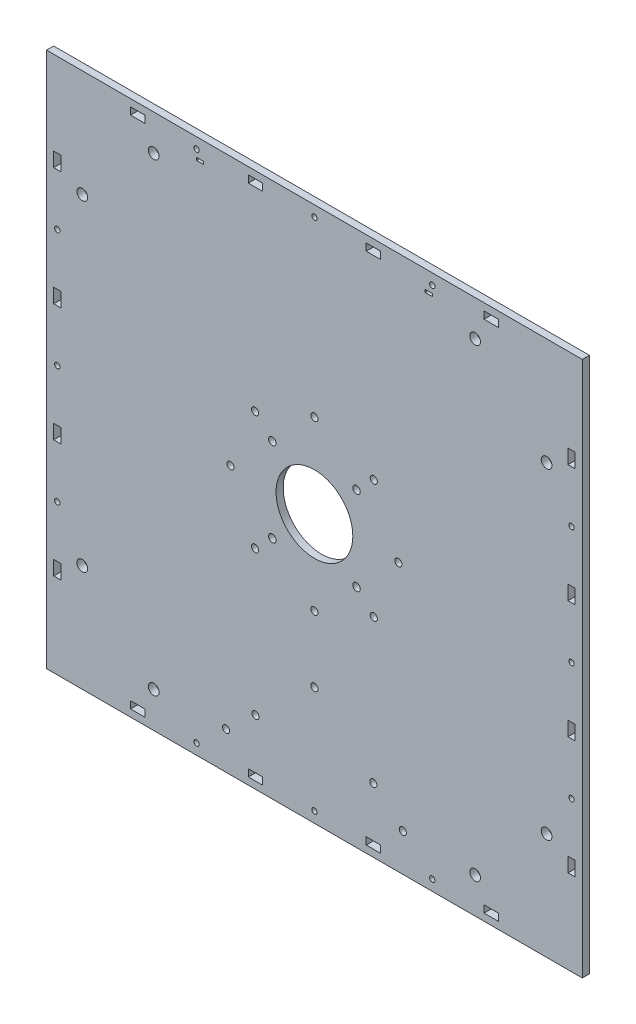
SolidWorks part; units mm, degrees
ref_plane "前视基准面" through (0, 0, 0) normal (0, 0, 1) x (1, 0, 0)
ref_plane "上视基准面" through (0, 0, 0) normal (0, 1, 0) x (1, 0, 0)
ref_plane "右视基准面" through (0, 0, 0) normal (1, 0, 0) x (0, 0, -1)
sketch "草图1" plane through (0, 0, 0) normal (0, 0, 1) x (1, 0, 0)
  line L0 (1.4571, -21.1871) -> (1.4571, -41.1871) construction
  line L1 (63.4571, 98.8129) -> (67.4571, 98.8129)
  line L2 (1.4571, -21.1871) -> (1.4571, 44.8129) construction
  line L3 (67.4571, 98.8129) -> (67.4571, 97.3129)
  line L4 (151.4571, -41.1871) -> (151.4571, 108.8129)
  line L5 (151.4571, 108.8129) -> (-148.5429, 108.8129)
  line L6 (-148.5429, 108.8129) -> (-148.5429, -191.1871)
  line L7 (-148.5429, -191.1871) -> (151.4571, -191.1871)
  line L8 (151.4571, -191.1871) -> (151.4571, -41.1871)
  line L9 (-148.5429, -41.1871) -> (-161.9412, -41.1871) construction
  line L10 (1.4571, -191.1871) -> (1.4571, -181.0361) construction
  line L11 (67.4571, 97.3129) -> (63.4571, 97.3129)
  line L12 (63.4571, 97.3129) -> (63.4571, 98.8129)
  line L13 (-64.5429, 98.8129) -> (-64.5429, 97.3129)
  line L14 (-64.5429, 97.3129) -> (-60.5429, 97.3129)
  line L15 (-60.5429, 97.3129) -> (-60.5429, 98.8129)
  line L16 (-60.5429, 98.8129) -> (-64.5429, 98.8129)
  circle A6 centre (1.4571, -21.1871) radius 241.4173 construction
  circle A9 centre (1.4571, -41.1871) radius 21.5
  circle A10 centre (25.0271, -17.6171) radius 2.1
  circle A11 centre (25.0271, -64.7571) radius 2.1
  circle A12 centre (-22.1129, -64.7571) radius 2.1
  circle A13 centre (-22.1129, -17.6171) radius 2.1
  dimension "D1" = 43
  dimension "D4" = 4.2
  dimension "D2" = 300
  dimension "D3" = 300
  dimension "D5" = 23.57
  dimension "D6" = 23.57
  dimension "D7" = 4
extrude "凸台-拉伸1" add sketch "草图1" along normal blind 4
sketch "草图3" plane through (0, 0, 4) normal (0, 0, 1) x (1, 0, 0)
  line L1 (96.4421, -183.1721) -> (104.4721, -183.1721)
  line L13 (1.4571, -191.1871) -> (1.4571, -185.1871) construction
  line L14 (-148.5429, -191.1871) -> (151.4571, -191.1871) construction
  line L15 (1.4571, -185.1871) -> (34.4571, -185.1871) construction
  line L16 (34.4571, -185.1871) -> (67.4571, -185.1871) construction
  line L17 (30.4421, -183.1721) -> (38.4721, -183.1721)
  line L18 (30.4421, -183.1721) -> (30.4421, -187.2021)
  line L19 (30.4421, -187.2021) -> (38.4721, -187.2021)
  line L20 (38.4721, -183.1721) -> (38.4721, -187.2021)
  line L21 (30.4421, -183.1721) -> (38.4721, -187.2021) construction
  line L22 (30.4421, -187.2021) -> (38.4721, -183.1721) construction
  line L23 (67.4571, -185.1871) -> (100.4571, -185.1871) construction
  line L24 (96.4421, -183.1721) -> (96.4421, -187.2021)
  line L25 (96.4421, -187.2021) -> (104.4721, -187.2021)
  line L26 (96.4421, -187.2021) -> (104.4721, -183.1721) construction
  line L27 (104.4721, -187.2021) -> (104.4721, -183.1721)
  line L28 (-35.5579, -183.1721) -> (-35.5579, -187.2021)
  line L29 (-27.5279, -183.1721) -> (-35.5579, -183.1721)
  line L30 (-27.5279, -183.1721) -> (-27.5279, -187.2021)
  line L31 (-27.5279, -187.2021) -> (-35.5579, -187.2021)
  line L32 (-93.5279, -183.1721) -> (-93.5279, -187.2021)
  line L33 (-101.5579, -187.2021) -> (-101.5579, -183.1721)
  line L34 (-93.5279, -183.1721) -> (-101.5579, -183.1721)
  line L35 (-93.5279, -187.2021) -> (-101.5579, -187.2021)
  line L36 (-140.5279, 53.7979) -> (-140.5279, 61.8279)
  line L37 (-144.5579, 53.7979) -> (-144.5579, 61.8279)
  line L38 (-144.5579, 61.8279) -> (-140.5279, 61.8279)
  line L39 (-140.5279, 53.7979) -> (-144.5579, 53.7979)
  line L40 (-140.5279, -12.2021) -> (-140.5279, -4.1721)
  line L41 (-140.5279, -4.1721) -> (-144.5579, -4.1721)
  line L42 (-144.5579, -12.2021) -> (-144.5579, -4.1721)
  line L43 (-140.5279, -12.2021) -> (-144.5579, -12.2021)
  line L44 (-140.5279, -70.1721) -> (-144.5579, -70.1721)
  line L45 (-140.5279, -70.1721) -> (-140.5279, -78.2021)
  line L46 (-144.5579, -70.1721) -> (-144.5579, -78.2021)
  line L47 (-140.5279, -78.2021) -> (-144.5579, -78.2021)
  line L48 (-140.5279, -136.1721) -> (-140.5279, -144.2021)
  line L49 (-144.5579, -136.1721) -> (-144.5579, -144.2021)
  line L50 (-140.5279, -136.1721) -> (-144.5579, -136.1721)
  line L51 (-144.5579, -144.2021) -> (-140.5279, -144.2021)
  line L52 (96.4421, 100.7979) -> (104.4721, 100.7979)
  line L53 (96.4421, 104.8279) -> (104.4721, 104.8279)
  line L54 (104.4721, 104.8279) -> (104.4721, 100.7979)
  line L55 (96.4421, 100.7979) -> (96.4421, 104.8279)
  line L56 (30.4421, 100.7979) -> (38.4721, 100.7979)
  line L57 (38.4721, 100.7979) -> (38.4721, 104.8279)
  line L58 (30.4421, 104.8279) -> (38.4721, 104.8279)
  line L59 (30.4421, 100.7979) -> (30.4421, 104.8279)
  line L60 (-27.5279, 100.7979) -> (-27.5279, 104.8279)
  line L61 (-27.5279, 100.7979) -> (-35.5579, 100.7979)
  line L62 (-27.5279, 104.8279) -> (-35.5579, 104.8279)
  line L63 (-35.5579, 100.7979) -> (-35.5579, 104.8279)
  line L64 (-93.5279, 100.7979) -> (-101.5579, 100.7979)
  line L65 (-93.5279, 104.8279) -> (-101.5579, 104.8279)
  line L66 (-93.5279, 100.7979) -> (-93.5279, 104.8279)
  line L67 (-101.5579, 104.8279) -> (-101.5579, 100.7979)
  line L68 (143.4421, -136.1721) -> (143.4421, -144.2021)
  line L69 (147.4721, -136.1721) -> (147.4721, -144.2021)
  line L70 (147.4721, -144.2021) -> (143.4421, -144.2021)
  line L71 (143.4421, -136.1721) -> (147.4721, -136.1721)
  line L72 (143.4421, -70.1721) -> (143.4421, -78.2021)
  line L73 (143.4421, -78.2021) -> (147.4721, -78.2021)
  line L74 (147.4721, -70.1721) -> (147.4721, -78.2021)
  line L75 (143.4421, -70.1721) -> (147.4721, -70.1721)
  line L76 (143.4421, -12.2021) -> (147.4721, -12.2021)
  line L77 (143.4421, -12.2021) -> (143.4421, -4.1721)
  line L78 (147.4721, -12.2021) -> (147.4721, -4.1721)
  line L79 (143.4421, -4.1721) -> (147.4721, -4.1721)
  line L80 (143.4421, 53.7979) -> (143.4421, 61.8279)
  line L81 (147.4721, 53.7979) -> (147.4721, 61.8279)
  line L82 (143.4421, 53.7979) -> (147.4721, 53.7979)
  line L83 (147.4721, 61.8279) -> (143.4421, 61.8279)
  line L84 (50.9571, -185.1871) -> (50.9571, -170.1871) construction
  line L85 (17.9571, -185.1871) -> (17.9571, -170.1871) construction
  line L86 (-48.0429, -170.1871) -> (-15.0429, -170.1871) construction
  line L91 (-31.5429, -170.1871) -> (-31.5429, -155.1871) construction
  circle A0 centre (1.4571, -185.1871) radius 1.5
  circle A1 centre (67.4571, -185.1871) radius 1.5
  circle A2 centre (-64.5429, -185.1871) radius 1.5
  circle A3 centre (-142.5429, 24.8129) radius 1.5
  circle A4 centre (-142.5429, -41.1871) radius 1.5
  circle A5 centre (-142.5429, -107.1871) radius 1.5
  circle A6 centre (67.4571, 102.8129) radius 1.5
  circle A7 centre (1.4571, 102.8129) radius 1.5
  circle A8 centre (-64.5429, 102.8129) radius 1.5
  circle A9 centre (145.4571, -107.1871) radius 1.5
  circle A10 centre (145.4571, -41.1871) radius 1.5
  circle A11 centre (145.4571, 24.8129) radius 1.5
  circle A15 centre (17.9571, -170.1871) radius 2 construction
  circle A16 centre (-15.0429, -170.1871) radius 2 construction
  circle A17 centre (50.9571, -170.1871) radius 2
  circle A18 centre (-48.0429, -170.1871) radius 2
  circle A19 centre (-31.5429, -155.1871) radius 2
  circle A20 centre (34.4571, -155.1871) radius 2
  circle A22 centre (1.4571, -155.1871) radius 2 construction
  circle A23 centre (1.4571, -41.1871) radius 47 construction
  circle A24 centre (1.4571, -88.1871) radius 2
  circle A25 centre (-31.7769, -74.4212) radius 2
  circle A26 centre (-45.5429, -41.1871) radius 2
  circle A27 centre (-31.7769, -7.9531) radius 2
  circle A28 centre (1.4571, 5.8129) radius 2
  circle A29 centre (34.6912, -7.9531) radius 2
  circle A30 centre (48.4571, -41.1871) radius 2
  circle A31 centre (34.6912, -74.4212) radius 2
  circle A32 centre (1.4571, -125.1871) radius 2
  dimension "D1" = 8.03
  dimension "D3" = 4
  dimension "D4" = 8
  dimension "D5" = 30
  dimension "D6" = 4
  dimension "D7" = 94
  dimension "D8" = 4
  dimension "D2" = 4.03
extrude "切除-拉伸2" cut sketch "草图3" against normal blind 4
sketch "草图6" plane through (0, 0, 4) normal (0, 0, 1) x (1, 0, 0)
sketch "草图7" plane through (0, 0, 4) normal (0, 0, 1) x (1, 0, 0)
  line L5 (-148.5429, -171.1871) -> (151.4571, -171.1871) construction
  line L6 (-148.5429, 108.8129) -> (-148.5429, -191.1871) construction
  line L7 (151.4571, -191.1871) -> (151.4571, 108.8129) construction
  line L8 (-148.5429, -191.1871) -> (151.4571, -191.1871) construction
  circle A0 centre (-88.5429, -171.1871) radius 3
  circle A1 centre (91.4571, -171.1871) radius 3
  circle A2 centre (-128.5429, 48.8129) radius 3
  circle A3 centre (-128.5429, -131.1871) radius 3
  circle A4 centre (91.4571, 88.8129) radius 3
  circle A5 centre (-88.5429, 88.8129) radius 3
  circle A6 centre (131.4571, -131.1871) radius 3
  circle A7 centre (131.4571, 48.8129) radius 3
  dimension "D2" = 6
  dimension "D4" = 60
  dimension "D1" = 20
  dimension "D3" = 60
  dimension "D5" = 4
extrude "切除-拉伸3" cut sketch "草图7" against normal blind 10
